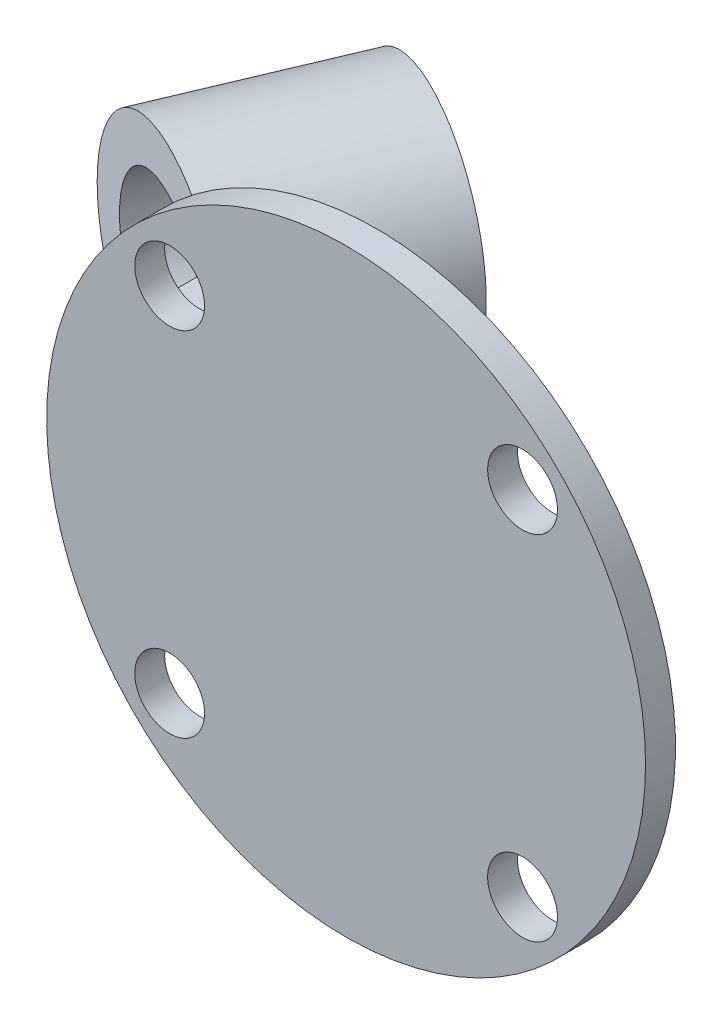
SolidWorks part; units mm, degrees
ref_plane "前视基准面" through (0, 0, 0) normal (0, 0, 1) x (1, 0, 0)
ref_plane "上视基准面" through (0, 0, 0) normal (0, 1, 0) x (1, 0, 0)
ref_plane "右视基准面" through (0, 0, 0) normal (1, 0, 0) x (0, 0, -1)
sketch "草图2" plane through (0, 0, 0) normal (0, 0, 1) x (1, 0, 0)
  circle A0 centre (0, 0) radius 30
  dimension "D1" = 60
extrude "凸台-拉伸1" add sketch "草图2" along normal blind 3 contours A0
sketch "草图3" plane through (0, 0, 3) normal (0, 0, 1) x (1, 0, 0)
  line L2 (0, -1.65) -> (0, 1.65) construction
  line L3 (1.65, 0) -> (-1.65, 0) construction
  circle A0 centre (-17.6777, 17.6777) radius 3.5
  circle A4 centre (17.6777, 17.6777) radius 3.5
  circle A5 centre (17.6777, -17.6777) radius 3.5
  circle A6 centre (-17.6777, -17.6777) radius 3.5
  dimension "D1" = 25
  dimension "D2" = 7
  dimension "D3" = 35.3553
  dimension "D4" = 35.3553
extrude "切除-拉伸1" cut sketch "草图3" against normal blind 3
sketch "草图4" plane through (0, 0, 0) normal (1, 0, 0) x (0, 0, -1)
  line L0 (-3, 30) -> (-3, -30) construction
  line L1 (0, -5) -> (-3, -5)
  line L2 (0, -5) -> (0, 5)
  line L3 (0, 5) -> (-3, 5)
  line L4 (-3, -5) -> (-3, 5)
  line L5 (0, -5) -> (-3, 5) construction
  line L6 (0, 5) -> (-3, -5) construction
  point P0 (-1.5, 0)
  dimension "D1" = 10
  dimension "D2" = 3
sketch "草图13" plane through (0, 0, 0) normal (0, 1, 0) x (1, 0, 0)
  line L0 (-35, 20) -> (0, 102.9156)
  line L1 (0, -58.2536) -> (0, 58.2536) construction
  line L2 (-35, 20) -> (0, 5.2259)
  line L3 (-47.85, 0) -> (47.85, 0) construction
  dimension "D1" = 35
  dimension "D2" = 90
  dimension "D3" = 0
  dimension "D4" = 20
  dimension "D5" = 90
  dimension "D6" = 0
  dimension "D7" = 82.9156
  dimension "D8" = 67.115
ref_plane "基准面2" through (1.8723, 0, -4.4356) normal (-0.3889, 0, 0.9213) x (0.9213, 0, 0.3889)
sketch "草图15" plane through (1.8723, 0, -4.4356) normal (-0.3889, 0, 0.9213) x (0.9213, 0, 0.3889)
  circle A0 centre (-40.0227, 0) radius 7.8
  circle A1 centre (-40.0227, 0) radius 15
  dimension "D1" = 15.6
  dimension "D2" = 30
ref_plane "基准面3" through (-0.0721, 0, 0.1708) normal (-0.3889, 0, 0.9213) x (0.9213, 0, 0.3889)
sketch "草图24" plane through (-0.0721, 0, 0.1708) normal (-0.3889, 0, 0.9213) x (0.9213, 0, 0.3889)
  circle A0 centre (-40.0227, 0) radius 15
  circle A1 centre (-40.0227, 0) radius 7.8
sketch "草图25" plane through (0, 0, 0) normal (0, 1, 0) x (1, 0, 0)
  line L0 (-29.7584, 12.3602) -> (-25.889, 10.7269)
  line L1 (-50.7637, 21.2269) -> (-23.1252, 9.5602) construction
  line L2 (-44.1305, 18.4269) -> (-29.7584, 12.3602) construction
  line L3 (-13.8658, 5.6517) -> (13.7216, -5.9934) construction
  line L4 (-25.889, 10.7269) -> (-18.1113, 29.1526)
  line L5 (-18.1113, 29.1526) -> (-21.478, 30.5738)
  line L6 (-21.478, 30.5738) -> (-29.7584, 12.3602)
  line L7 (-35, 20) -> (-36.9444, 15.3936)
  line L8 (-42.186, 23.0333) -> (-27.814, 16.9667) construction
  dimension "D1" = 20
  dimension "D2" = 3.6544
  dimension "D3" = 4.2
revolve "旋转2" add sketch "草图25" angle 360 about L7
sketch "草图26" plane through (0, 0, 0) normal (0, 1, 0) x (1, 0, 0)
  line L0 (-29.7584, 12.3602) -> (-29.7584, 0)
  line L1 (30, 0) -> (-30, 0) construction
  line L2 (-29.7584, 0) -> (0, 0)
  line L3 (0, 0) -> (-23.9446, 15.3333)
  line L4 (-48.8193, 25.8333) -> (-21.1807, 14.1667) construction
  line L5 (-25.889, 10.7269) -> (-18.1113, 29.1526) construction
  line L7 (-23.9446, 15.3333) -> (-27.1599, 16.6906)
  line L8 (-27.1599, 16.6906) -> (-29.7584, 12.3602)
extrude "凸台-拉伸2" add sketch "草图26" along normal mid plane 10
